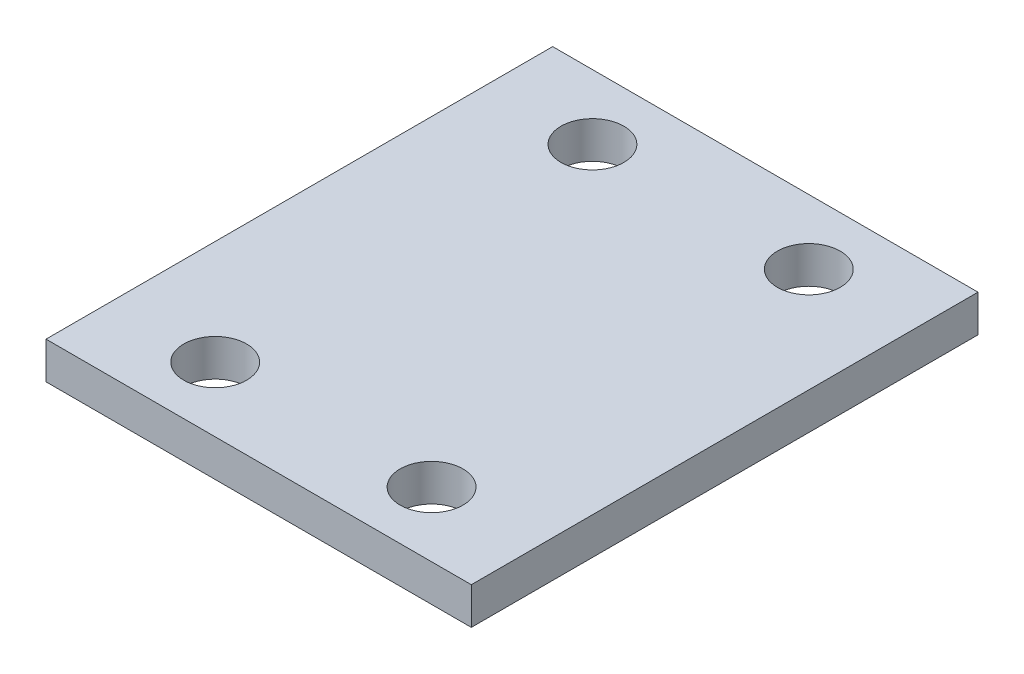
SolidWorks part; units mm, degrees
ref_plane "Front Plane" through (0, 0, 0) normal (0, 0, 1) x (1, 0, 0)
ref_plane "Top Plane" through (0, 0, 0) normal (0, 1, 0) x (1, 0, 0)
ref_plane "Right Plane" through (0, 0, 0) normal (1, 0, 0) x (0, 0, -1)
sketch "Sketch1" plane through (0, 0, 0) normal (0, 1, 0) x (1, 0, 0)
  line L0 (0, 13.8) -> (0, 0) construction
  line L1 (-11.7, 13.8) -> (11.7, 13.8)
  line L2 (-11.7, 13.8) -> (-11.7, -13.8)
  line L3 (-11.7, -13.8) -> (11.7, -13.8)
  line L4 (11.7, 13.8) -> (11.7, -13.8)
  line L5 (-11.7, 13.8) -> (11.7, -13.8) construction
  line L6 (-11.7, -13.8) -> (11.7, 13.8) construction
  line L7 (0, 10.2) -> (-11.7, 10.2) construction
  line L8 (0, 0) -> (11.7, 0) construction
  line L10 (-11.5, 13.7) -> (11.5, 13.7)
  line L11 (-11.5, 13.7) -> (-11.5, -13.7)
  line L12 (-11.5, -13.7) -> (11.5, -13.7)
  line L13 (11.5, 13.7) -> (11.5, -13.7)
  circle A0 centre (-5.85, 10.2) radius 1.7
  circle A4 centre (5.85, 10.2) radius 1.7
  circle A5 centre (5.85, -10.2) radius 1.7
  circle A6 centre (-5.85, -10.2) radius 1.7
  point P0 (0, 0)
  dimension "D4" = 3.4
  dimension "D1" = 23.4
  dimension "D2" = 27.6
  dimension "D3" = 10.2
  dimension "D5" = 5.85
  dimension "D6" = 0.2
  dimension "D7" = 0.1
  dimension "D8" = 0.1
  dimension "D9" = 0.2
extrude "Boss-Extrude1" add sketch "Sketch1" against normal blind 2 contours L13 L10 L11 L12 A4 A0 A5 A6
